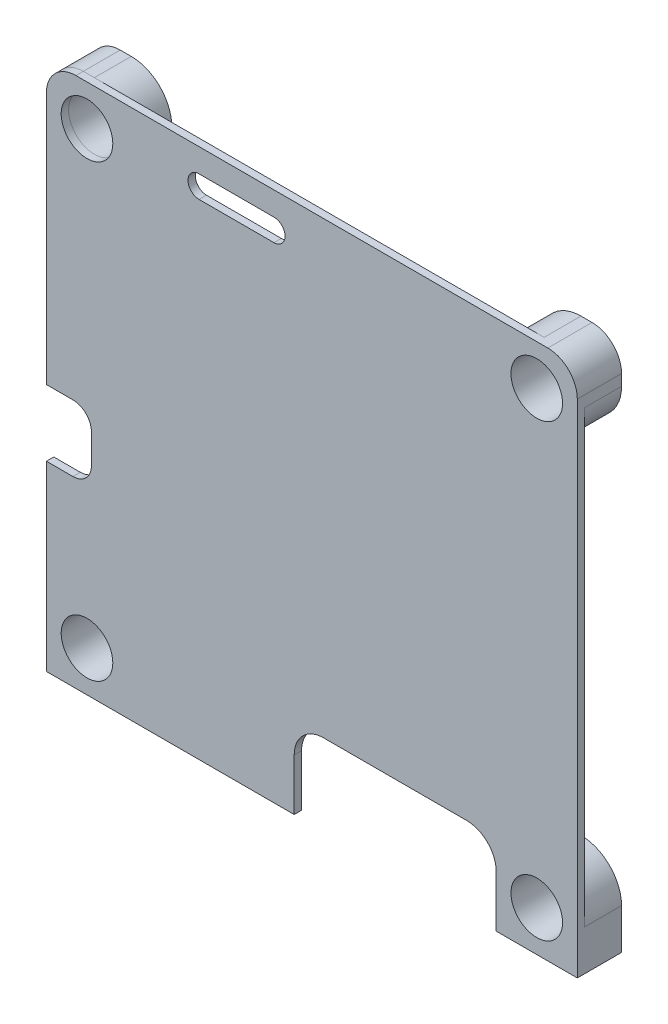
SolidWorks part; units mm, degrees
ref_plane "Front Plane" through (0, 0, 0) normal (0, 0, 1) x (1, 0, 0)
ref_plane "Top Plane" through (0, 0, 0) normal (0, 1, 0) x (1, 0, 0)
ref_plane "Right Plane" through (0, 0, 0) normal (1, 0, 0) x (0, 0, -1)
sketch "Sketch2" plane through (0, 0, 0) normal (0, 0, 1) x (1, 0, 0)
  line L1 (12.5, -18) -> (18, -18)
  line L2 (12.5, -18) -> (12.5, -12.5)
  line L3 (12.5, -12.5) -> (18, -12.5)
  line L4 (16, 18) -> (-16, 18)
  line L5 (-18, 16) -> (-18, -16)
  line L6 (-16, -18) -> (16, -18)
  line L7 (18, -16) -> (18, 16)
  line L8 (16, 18) -> (-16, 18)
  line L9 (-18, 16) -> (-18, -16)
  line L10 (-16, -18) -> (16, -18)
  line L11 (18, -16) -> (18, 16)
  line L12 (18, -18) -> (18, -12.5)
  line L13 (12.5, -18) -> (18, -12.5) construction
  line L14 (12.5, -12.5) -> (18, -18) construction
  line L15 (-12.5, -18) -> (-18, -18)
  line L16 (-12.5, -18) -> (-12.5, -12.5)
  line L17 (-12.5, -12.5) -> (-18, -12.5)
  line L18 (-18, -18) -> (-18, -12.5)
  line L19 (-12.5, -18) -> (-18, -12.5) construction
  line L20 (-12.5, -12.5) -> (-18, -18) construction
  circle A0 centre (15.25, -15.25) radius 2.75
  circle A1 centre (15.25, 15.25) radius 2.75
  circle A2 centre (-15.25, 15.25) radius 2.75
  circle A3 centre (-15.25, -15.25) radius 2.75
  arc A4 (-16, 18) -> (-18, 16) centre (-16, 16) ccw
  arc A5 (-18, -16) -> (-16, -18) centre (-16, -16) ccw
  arc A6 (16, -18) -> (18, -16) centre (16, -16) ccw
  arc A7 (18, 16) -> (16, 18) centre (16, 16) ccw
  arc A8 (-16, 18) -> (-18, 16) centre (-16, 16) ccw
  arc A9 (-18, -16) -> (-16, -18) centre (-16, -16) ccw
  arc A10 (16, -18) -> (18, -16) centre (16, -16) ccw
  arc A11 (18, 16) -> (16, 18) centre (16, 16) ccw
  circle A20 centre (-15.25, 15.25) radius 1.75
  circle A21 centre (15.25, 15.25) radius 1.75
  circle A22 centre (15.25, -15.25) radius 1.75
  circle A23 centre (-15.25, -15.25) radius 1.75
  circle M9 centre (15.25, -15.25) radius 1.5
  circle M10 centre (-15.25, 15.25) radius 1.5
  line M11 (16, 18) -> (-16, 18)
  arc M12 (-16, 18) -> (-18, 16) centre (-16, 16) ccw
  line M13 (-18, 16) -> (-18, -16)
  arc M14 (-18, -16) -> (-16, -18) centre (-16, -16) ccw
  line M15 (-16, -18) -> (16, -18)
  arc M16 (16, -18) -> (18, -16) centre (16, -16) ccw
  line M17 (18, -16) -> (18, 16)
  arc M18 (18, 16) -> (16, 18) centre (16, 16) ccw
  circle M19 centre (15.25, 15.25) radius 1.5
  circle M20 centre (-15.25, -15.25) radius 1.5
  dimension "D2" = 3.5
  dimension "D1" = 0
extrude "Standoffs" add sketch "Sketch2" along normal blind 2.5 contours A0 M9 | A0 L10 M16 M17 | A1 M19 | A1 M17 M18 M11 | A2 M10 | A2 M11 M12 M13 | A3 M20 | A3 M13 M14 M15 | L1 L12 M16 | A0 L2 M15 | L18 L15 M14 | A3 L15 L16
sketch "Sketch3" plane through (0, 0, 2.5) normal (0, 0, 1) x (1, 0, 0)
  line L0 (-18, -15.25) -> (-18, -18) construction
  line L1 (-18, -18) -> (-12.5, -18) construction
  line L2 (12.5, -18) -> (18, -18) construction
  line L3 (18, -18) -> (18, -15.25) construction
  line L4 (18, 15.25) -> (18, 16) construction
  line L5 (16, 18) -> (15.25, 18) construction
  line L6 (-15.25, 18) -> (-16, 18) construction
  line L7 (-18, 16) -> (-18, 15.25) construction
  line L8 (-18, -15.25) -> (-18, -18)
  line L9 (-18, -18) -> (-12.5, -18)
  line L10 (12.5, -18) -> (18, -18)
  line L11 (18, -18) -> (18, -15.25)
  line L12 (18, 15.25) -> (18, 16)
  line L13 (16, 18) -> (15.25, 18)
  line L14 (-15.25, 18) -> (-16, 18)
  line L15 (-18, 16) -> (-18, 15.25)
  line L16 (-18, 15.25) -> (-18, -15.25)
  line L17 (-15.25, 18) -> (15.25, 18)
  line L18 (18, 15.25) -> (18, -15.25)
  line L19 (12.5, -15.25) -> (12.5, -12.5)
  line L20 (12.5, -12.5) -> (-1.2, -12.5)
  line L21 (-2.3, -18.1) -> (13.6, -18.1) construction
  line L22 (5.65, -18.1) -> (5.65, -12.5) construction
  line L23 (15.25, -12.5) -> (12.5, -12.5) construction
  line L24 (-1.2, -12.5) -> (-1.2, -18)
  line L25 (-12.5, -18) -> (-1.2, -18)
  line L26 (13.6, -18) -> (13.6, -34.2) construction
  line L27 (12.5, -12.5) -> (18, -12.5)
  line L28 (12.5, -12.5) -> (12.5, -18)
  line L29 (12.5, -18) -> (18, -18)
  line L30 (18, -12.5) -> (18, -18)
  line L31 (13.6, -34.2) -> (13.6, -18.1) construction
  line L32 (-16.2, -2.4) -> (-16.2, -4.4) construction
  line L33 (-14.95, -2.4) -> (-14.95, -4.4)
  line L34 (-17.45, -2.4) -> (-17.45, -4.4)
  line L35 (-7.65, 15.65) -> (-2.57, 15.65) construction
  line L36 (-7.65, 16.4) -> (-2.57, 16.4)
  line L37 (-7.65, 14.9) -> (-2.57, 14.9)
  line L38 (-16.2, -1.15) -> (-18, -1.15)
  line L39 (-16.2, -5.65) -> (-18, -5.65)
  arc A0 (-7.65, 16.4) -> (-7.65, 14.9) centre (-7.65, 15.65) ccw
  arc A1 (-2.57, 14.9) -> (-2.57, 16.4) centre (-2.57, 15.65) ccw
  circle A2 centre (-7.65, 15.65) radius 0.6 construction
  circle A3 centre (-7.65, 15.65) radius 0.6
  arc A4 (15.25, 18) -> (18, 15.25) centre (15.25, 15.25) ccw construction
  arc A5 (18, 16) -> (16, 18) centre (16, 16) ccw construction
  arc A6 (-18, 15.25) -> (-15.25, 18) centre (-15.25, 15.25) ccw construction
  arc A7 (-16, 18) -> (-18, 16) centre (-16, 16) ccw construction
  circle A8 centre (-16.2, -3.4) radius 1.25
  arc A9 (-14.95, -2.4) -> (-17.45, -2.4) centre (-16.2, -2.4) ccw
  arc A10 (-17.45, -4.4) -> (-14.95, -4.4) centre (-16.2, -4.4) ccw
  circle A11 centre (-2.57, 15.65) radius 0.6 construction
  arc A12 (15.25, 18) -> (18, 15.25) centre (15.25, 15.25) ccw
  arc A13 (18, 16) -> (16, 18) centre (16, 16) ccw
  arc A14 (-18, 15.25) -> (-15.25, 18) centre (-15.25, 15.25) ccw
  arc A15 (-16, 18) -> (-18, 16) centre (-16, 16) ccw
  circle A20 centre (-15.25, -15.25) radius 1.75 construction
  circle A21 centre (15.25, -15.25) radius 1.75 construction
  circle A22 centre (15.25, 15.25) radius 1.75 construction
  circle A23 centre (-15.25, 15.25) radius 1.75 construction
  circle A24 centre (-2.57, 15.65) radius 0.6
  circle A25 centre (-15.25, -15.25) radius 1.75
  circle A26 centre (15.25, -15.25) radius 1.75
  circle A27 centre (15.25, 15.25) radius 1.75
  circle A28 centre (-15.25, 15.25) radius 1.75
  point P33 (5.65, -12.5)
  point P50 (-16.2, -3.4)
  point P56 (-5.11, 15.65)
  dimension "D1" = 2.5
  dimension "D2" = 21.4
  dimension "D3" = 1.8
  dimension "D4" = 2
  dimension "D5" = 1.5
extrude "Cover" add sketch "Sketch3" along normal blind 0.5
fillet "Fillets" radius 2 2 edges at (12.5, -12.5, 2.75) (-1.2, -12.5, 2.75)
